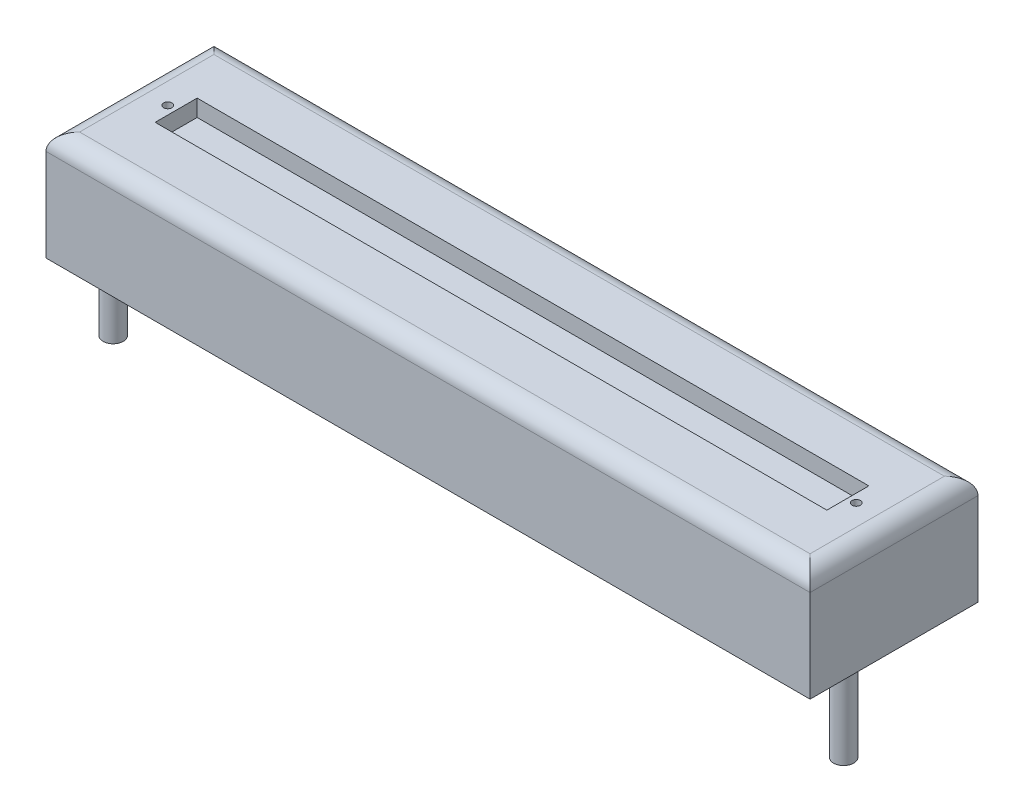
SolidWorks part; units mm, degrees
ref_plane "Front Plane" through (0, 0, 0) normal (0, 0, 1) x (1, 0, 0)
ref_plane "Top Plane" through (0, 0, 0) normal (0, 1, 0) x (1, 0, 0)
ref_plane "Right Plane" through (0, 0, 0) normal (1, 0, 0) x (0, 0, -1)
sketch "Sketch1" plane through (0, 0, 0) normal (0, 1, 0) x (1, 0, 0)
  line L0 (-22.75, 5) -> (22.75, -5) construction
  line L1 (-22.75, 5) -> (22.75, 5)
  line L2 (-22.75, 5) -> (-22.75, -5)
  line L3 (-22.75, -5) -> (22.75, -5)
  line L4 (22.75, 5) -> (22.75, -5)
  line L5 (-55, 0) -> (55, 0) construction
  line L6 (-20.5, 0) -> (20.5, 0) construction
  line L7 (0, -55) -> (0, 55) construction
  circle A0 centre (-20.5, 0) radius 0.25
  circle A1 centre (20.5, 0) radius 0.25
  dimension "D4" = 0.5
  dimension "D1" = 10
  dimension "D2" = 45.5
  dimension "D3" = 20.5
extrude "Boss-Extrude1" add sketch "Sketch1" along normal blind 6.5
sketch "Sketch2" plane through (0, 0, 0) normal (0, -1, 0) x (1, 0, 0)
  line L6 (-21.75, 2) -> (21.75, 2) construction
  line L7 (-21.75, -2) -> (21.75, -2) construction
  line L8 (-21.75, 2) -> (21.75, -2) construction
  line L9 (21.75, -2) -> (21.75, 2) construction
  line L10 (-21.75, -2) -> (-21.75, 2) construction
  circle A5 centre (-21.75, 2) radius 0.6
  circle A6 centre (-21.75, -2) radius 0.6
  circle A9 centre (21.75, 2) radius 0.6
  dimension "D5" = 1.2
  dimension "D1" = 43.5
  dimension "D7" = 4
extrude "Boss-Extrude2" add sketch "Sketch2" along normal blind 5
sketch "Sketch3" plane through (0, 0, 0) normal (0, -1, 0) x (1, 0, 0)
  line L0 (-15.9497, 1) -> (27.7052, 1) construction
  text T0 "1                                             3\r\n2                                             2\r\n" font "Century Gothic" height 2
sketch "Sketch4" plane through (0, 6.5, 0) normal (0, 1, 0) x (1, 0, 0)
  line L0 (-20, 1.25) -> (20, -1.25) construction
  line L1 (-20, 1.25) -> (20, 1.25)
  line L2 (-20, 1.25) -> (-20, -1.25)
  line L3 (-20, -1.25) -> (20, -1.25)
  line L4 (20, 1.25) -> (20, -1.25)
  dimension "D1" = 2.5
  dimension "D2" = 40
extrude "Cut-Extrude1" cut sketch "Sketch4" against normal blind 1
fillet "Fillet1" radius 1 4 edges at (22.75, 6.5, 0) (0, 6.5, -5) (0, 6.5, 5) (-22.75, 6.5, 0)
